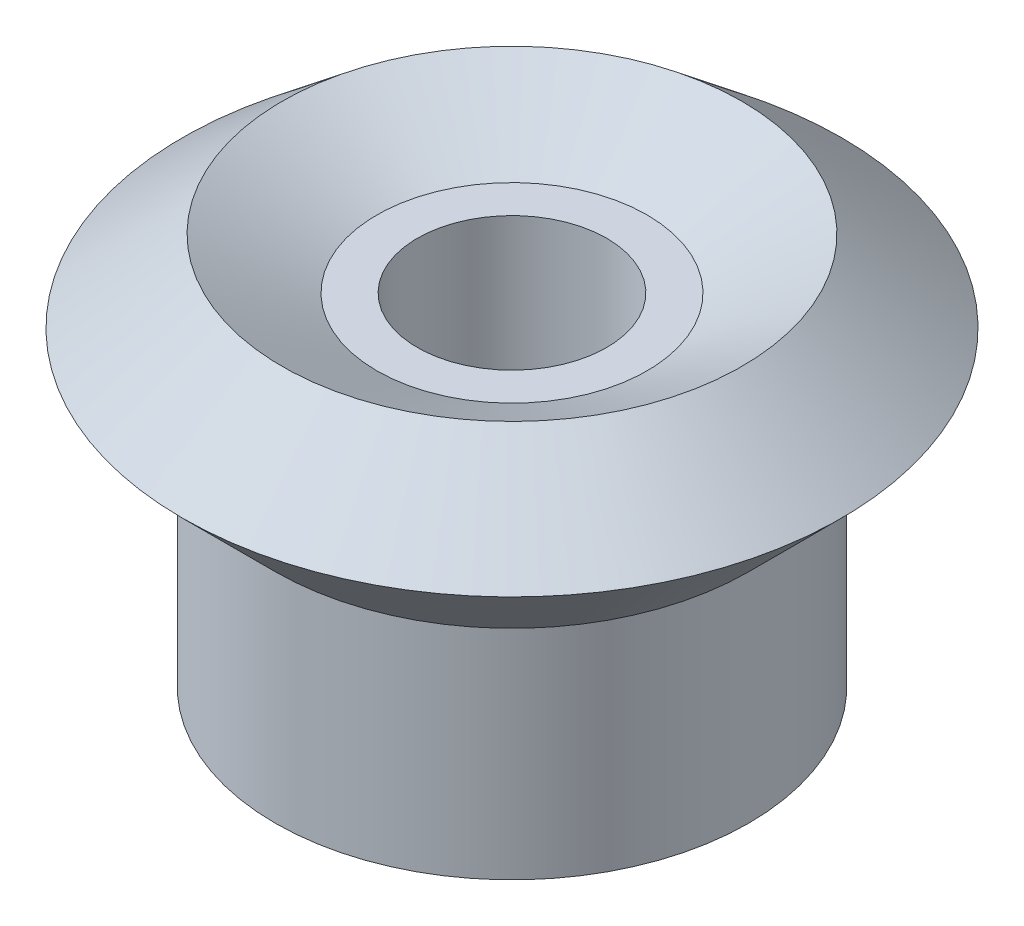
SolidWorks part; units mm, degrees
ref_plane "Front Plane" through (0, 0, 0) normal (0, 0, 1) x (1, 0, 0)
ref_plane "Top Plane" through (0, 0, 0) normal (0, 1, 0) x (1, 0, 0)
ref_plane "Right Plane" through (0, 0, 0) normal (1, 0, 0) x (0, 0, -1)
sketch "Sketch1" plane through (0, 0, 0) normal (0, 0, 1) x (1, 0, 0)
  line L0 (17.4, 16.4) -> (12.1322, 20.7)
  line L1 (12.1322, 20.7) -> (7.1322, 18)
  line L2 (7.1322, 18) -> (5, 18)
  line L3 (5, 18) -> (5, 0)
  line L4 (5, 0) -> (12.5, 0)
  line L5 (12.5, 0) -> (12.5, 11.5)
  line L6 (12.5, 11.5) -> (17.4, 16.4)
  line L7 (0, 20.7) -> (0, 0) construction
revolve "Revolve1" add sketch "Sketch1" angle 360 about L7
sketch "Sketch3" plane through (0, 0, 0) normal (0, -1, 0) x (1, 0, 0)
  circle A0 centre (0, 0) radius 7.5
  dimension "D1" = 15
extrude "Cut-Extrude1" [suppressed] cut sketch "Sketch3" against normal through all
